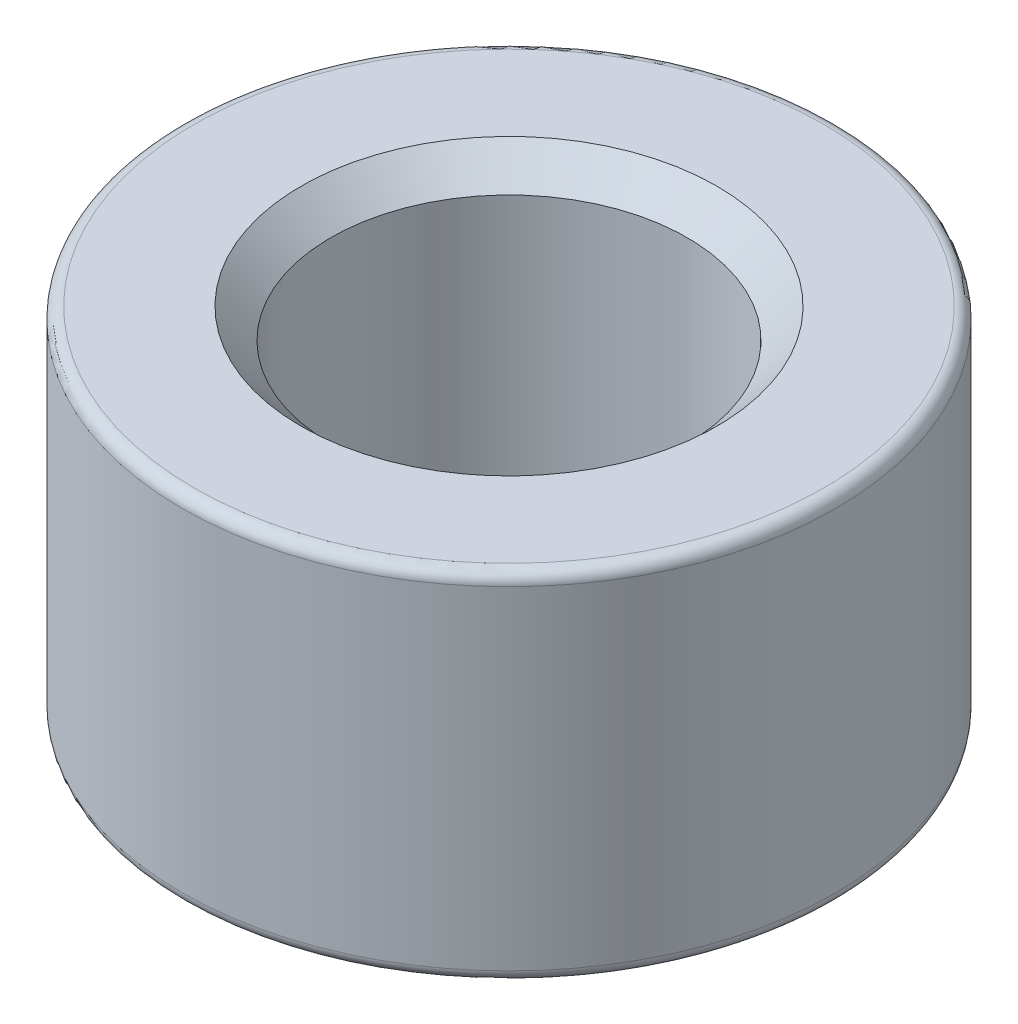
SolidWorks part; units mm, degrees
material "ASTM A36 Steel"
ref_plane "Front Plane" through (0, 0, 0) normal (0, 0, 1) x (1, 0, 0)
ref_plane "Top Plane" through (0, 0, 0) normal (0, 1, 0) x (1, 0, 0)
ref_plane "Right Plane" through (0, 0, 0) normal (1, 0, 0) x (0, 0, -1)
sketch "Sketch1" plane through (0, 0, 0) normal (0, 1, 0) x (1, 0, 0)
  circle A0 centre (0, 0) radius 2.75
  circle A1 centre (0, 0) radius 1.5
  dimension "D1" = 3
  dimension "D2" = 5.5
extrude "Boss-Extrude1" add sketch "Sketch1" along normal mid plane 3
chamfer "Chamfer1" distance 0.25 angle 45 2 edges at (0, -1.5, 1.5) (0, 1.5, 1.5)
fillet "Fillet1" radius 0.1 2 edges at (0, -1.5, 2.75) (0, 1.5, 2.75)
